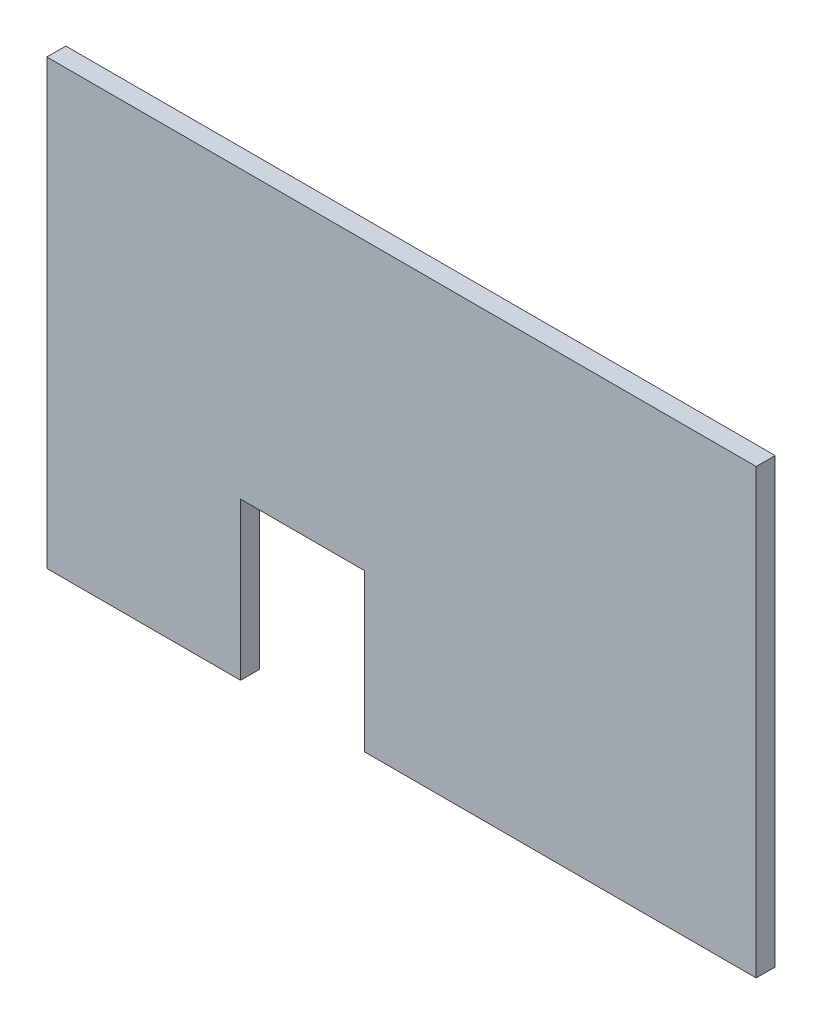
SolidWorks part; units mm, degrees
material "Cedro"
ref_plane "Plano frontal" through (0, 0, 0) normal (0, 0, 1) x (1, 0, 0)
ref_plane "Plano superior" through (0, 0, 0) normal (0, 1, 0) x (1, 0, 0)
ref_plane "Plano direito" through (0, 0, 0) normal (1, 0, 0) x (0, 0, -1)
sketch "Esboço2" plane through (0, 0, -150) normal (0, 0, -1) x (-1, 0, 0)
  line L0 (13.9303, -35) -> (44.55, -35)
  line L1 (-67.55, 35) -> (44.55, 35)
  line L2 (-67.55, 35) -> (-67.55, -35)
  line L3 (-67.55, -35) -> (-5.6756, -35)
  line L4 (44.55, 35) -> (44.55, -35)
  line L5 (-5.6756, -10.2051) -> (13.9303, -10.2051)
  line L6 (-5.6756, -10.2051) -> (-5.6756, -35)
  line L8 (13.9303, -10.2051) -> (13.9303, -35)
ref_plane "Plano1" through (-44.55, -35, -150) normal (0, 1, 0) x (1, 0, 0)
ref_plane "Plano2" through (-44.55, -35, -150) normal (-1, 0, 0) x (0, 0, 1)
extrude "Ressalto-extrusão1" add sketch "Esboço2" along normal blind 3
